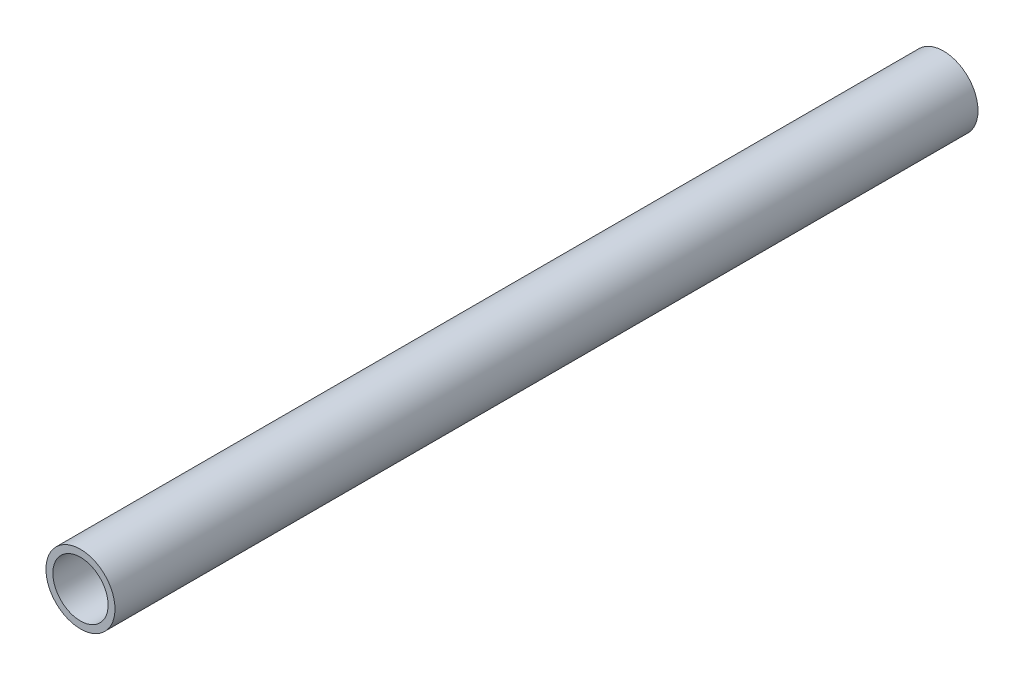
SolidWorks part; units mm, degrees
material "EM-CF"
ref_plane "Płaszczyzna przednia" through (0, 0, 0) normal (0, 0, 1) x (1, 0, 0)
ref_plane "Płaszczyzna górna" through (0, 0, 0) normal (0, 1, 0) x (1, 0, 0)
ref_plane "Płaszczyzna prawa" through (0, 0, 0) normal (1, 0, 0) x (0, 0, -1)
sketch "Szkic1" plane through (0, 0, 0) normal (0, 0, 1) x (1, 0, 0)
  circle A0 centre (0, 0) radius 8
  circle A1 centre (0, 0) radius 10
  dimension "D1" = 2
  dimension "D2" = 20
extrude "Dodanie-wyciągnięcie1" add sketch "Szkic1" along normal blind 250
